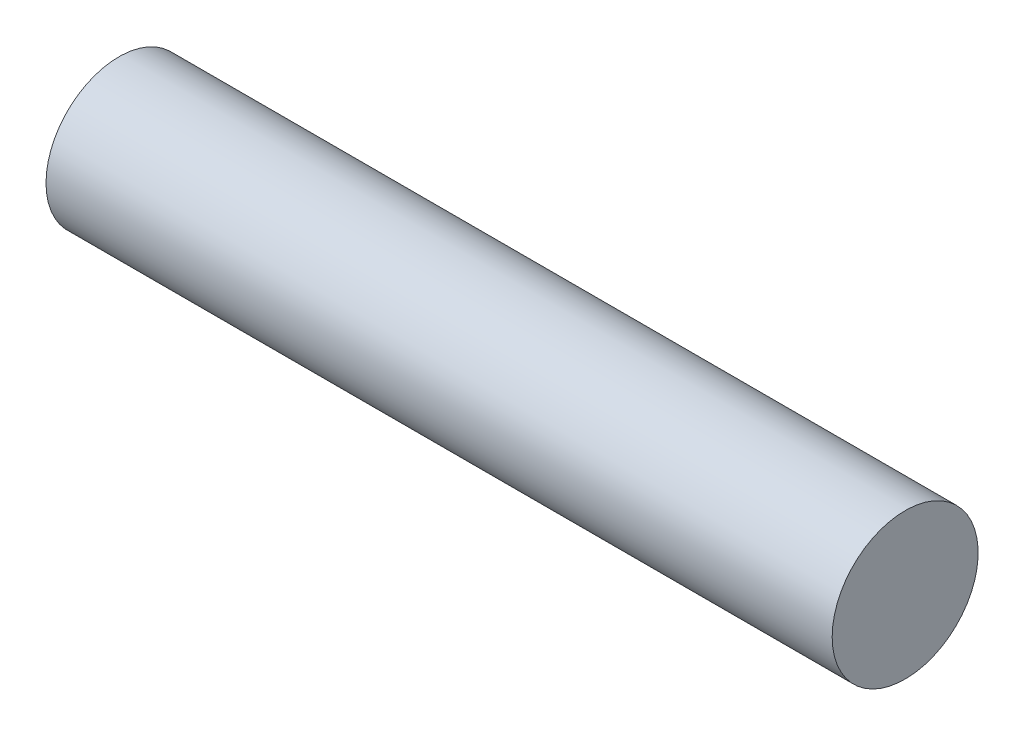
SolidWorks part; units mm, degrees
ref_plane "Plan de face" through (0, 0, 0) normal (0, 0, 1) x (1, 0, 0)
ref_plane "Plan de dessus" through (0, 0, 0) normal (0, 1, 0) x (1, 0, 0)
ref_plane "Plan de droite" through (0, 0, 0) normal (1, 0, 0) x (0, 0, -1)
sketch "Esquisse1" plane through (0, 0, 0) normal (0, 0, 1) x (1, 0, 0)
  line L1 (-34.1918, 39.0314) -> (-511.0456, 39.0314)
  line L2 (-511.0456, 39.0314) -> (-511.0456, -5.2397)
  line L4 (-511.0456, -5.2397) -> (-34.1918, -5.2397)
  line L6 (-34.1918, -5.2397) -> (-34.1918, 39.0314)
revolve "Révolution1" add sketch "Esquisse1" angle 360 about L4
